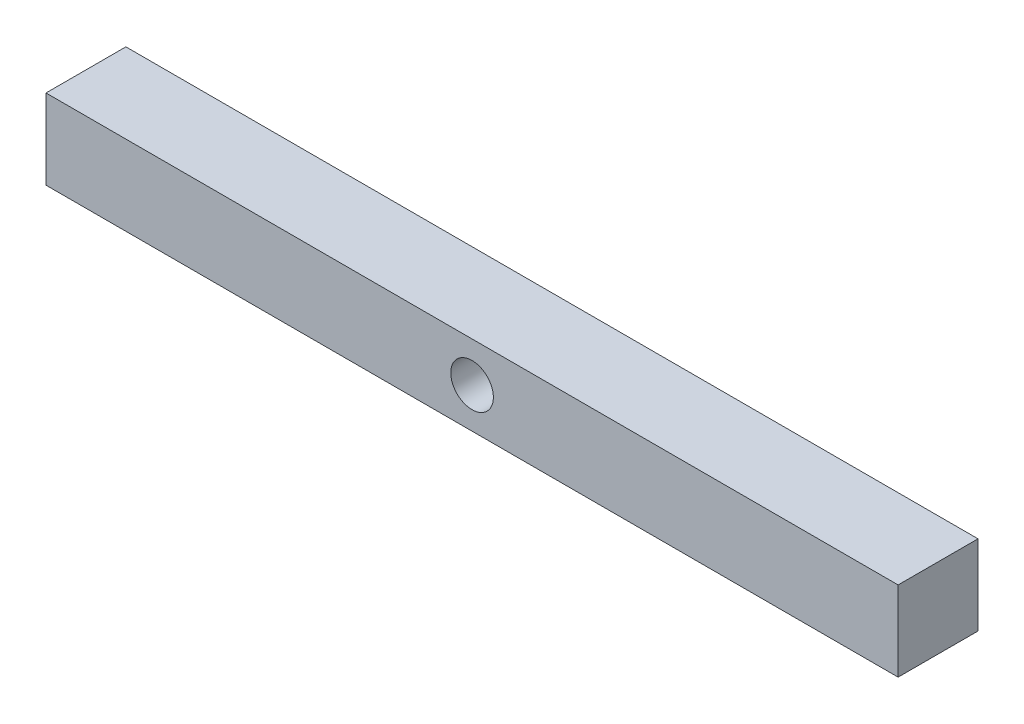
SolidWorks part; units mm, degrees
ref_plane "Plan de face" through (0, 0, 0) normal (0, 0, 1) x (1, 0, 0)
ref_plane "Plan de dessus" through (0, 0, 0) normal (0, 1, 0) x (1, 0, 0)
ref_plane "Plan de droite" through (0, 0, 0) normal (1, 0, 0) x (0, 0, -1)
sketch "Esquisse1" plane through (0, 0, 0) normal (0, 1, 0) x (1, 0, 0)
  line L0 (0, 0) -> (32, 0)
  line L1 (32, 0) -> (32, 3)
  line L2 (32, 3) -> (0, 3)
  line L3 (0, 3) -> (0, 0)
  dimension "D1" = 32
  dimension "D2" = 3
extrude "Boss.-Extru.1" add sketch "Esquisse1" along normal blind 2 and the other way blind 1
sketch "Esquisse2" plane through (0, 0, 0) normal (0, 0, 1) x (1, 0, 0)
  line L0 (32, 0.5) -> (16, 0.5) construction
  line L1 (32, -1) -> (32, 2) construction
  dimension "D1" = 16
hole_wizard "Dégagement M1.61" positions "Esquisse3D2" profile "Esquisse3" hole size "M1.6" standard "Ansi Metric" end condition up to next
sketch3d "Esquisse3D2"
  point P0 (16, 0.5, 0)
sketch "Esquisse3" plane through (16, 0.5, 0) normal (1, 0, 0) x (0, -1, 0)
  line L0 (0, 0) -> (0, 3)
  line L1 (0, 3) -> (0.8, 3)
  line L2 (0.8, 3) -> (0.8, 0)
  line L5 (0.8, 0) -> (0, 0)
  line L11 (0, -6.35) -> (0, 107.95) construction
  dimension "Diamètre du perçage jusqu'au prochain" = 1.6
  dimension "Profondeur du perçage jusqu'au prochain" = 3
